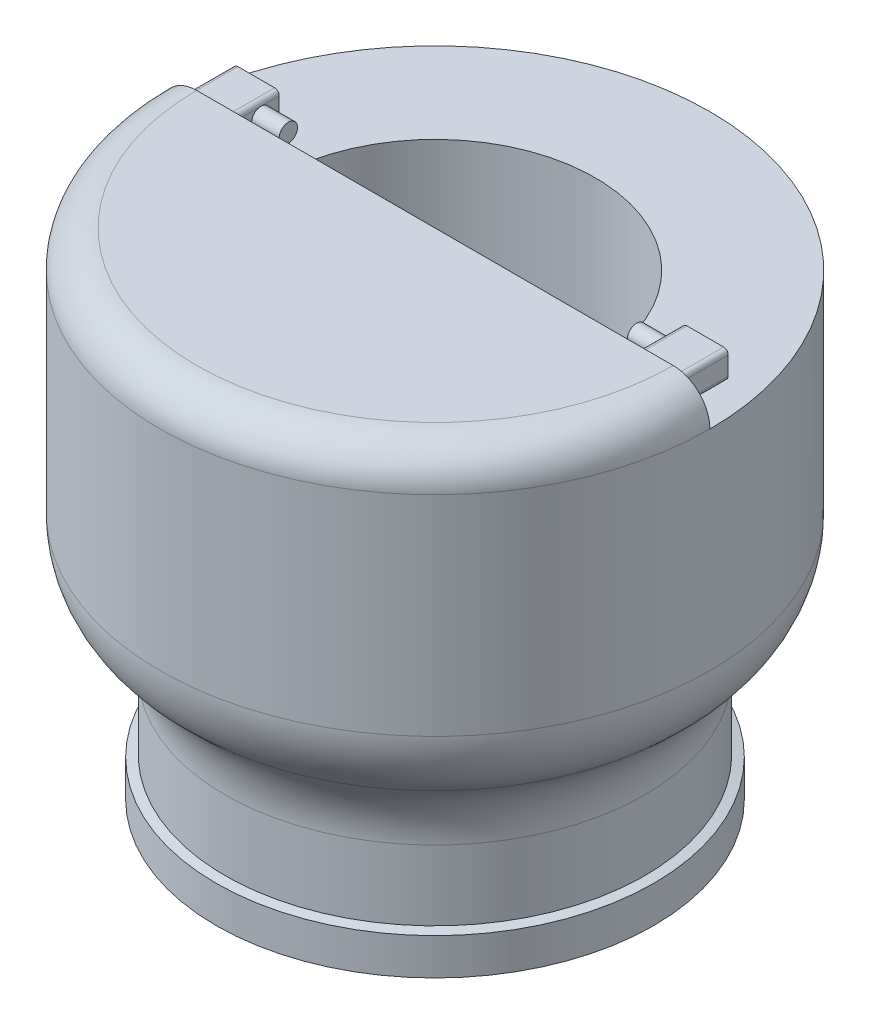
SolidWorks part; units mm, degrees
ref_plane "Front Plane" through (0, 0, 0) normal (0, 0, 1) x (1, 0, 0)
ref_plane "Top Plane" through (0, 0, 0) normal (0, 1, 0) x (1, 0, 0)
ref_plane "Right Plane" through (0, 0, 0) normal (1, 0, 0) x (0, 0, -1)
sketch "Sketch1" plane through (0, 0, 0) normal (0, 0, 1) x (1, 0, 0)
  line L0 (0, 0) -> (0, 57.8936) construction
  line L1 (20.9, 0) -> (23.8716, 0)
  line L2 (23.8716, 0) -> (23.8716, 4)
  line L3 (23.8716, 4) -> (22.9, 4.2367)
  line L4 (22.9, 4.2367) -> (22.9, 11.8746)
  line L6 (20.9, 0) -> (20.9, 14)
  line L12 (19.9, 15) -> (0, 15)
  line L17 (26.4721, 19.535) -> (26.4279, 19.4979)
  line L18 (30, 27.1583) -> (30, 50)
  line L20 (26, 54) -> (0, 54)
  line L22 (0, 15) -> (0, 54)
  arc A1 (30, 50) -> (26, 54) centre (26, 50) ccw
  arc A2 (26.4721, 19.535) -> (22.9, 11.8746) centre (32.9, 11.8746) ccw
  arc A3 (26.4279, 19.4979) -> (30, 27.1583) centre (20, 27.1583) ccw
  arc A6 (20.9, 14) -> (19.9, 15) centre (19.9, 14) ccw
  point P11 (22.9, 54)
  point P28 (28.5604, 23.4279)
  point P31 (20.9, 17)
  dimension "D9" = 4
  dimension "D4" = 30
  dimension "D16" = 10
  dimension "D19" = 1
  dimension "D2" = 4
  dimension "D3" = 1
  dimension "D6" = 2
  dimension "D7" = 2.9716
  dimension "D11" = 15
  dimension "D15" = 10
revolve "Revolve1" add sketch "Sketch1" angle 360 about L0
ref_plane "Plane1" through (0, 4, 0) normal (0, 1, 0) x (1, 0, 0)
sketch "Sketch3" plane through (0, 0, 0) normal (0, 0, 1) x (1, 0, 0)
  point P0 (1.2404, 19.1989)
ref_point "Point1"
ref_plane "Plane2" through (0, 0, 22.9) normal (0, 0, 1) x (1, 0, 0)
ref_plane "Plane3" through (0, 0, 30) normal (0, 0, 1) x (1, 0, 0)
ref_plane "Plane4" through (0, 50, 0) normal (0, -1, 0) x (-1, 0, 0)
sketch "Sketch9" plane through (0, 50, 0) normal (0, -1, 0) x (-1, 0, 0)
  line L0 (-30, 0) -> (30, 0)
  arc A0 (30, 0) -> (-30, 0) centre (0, 0) ccw
  circle A3 centre (0, 0) radius 26 construction
  dimension "D1" = 60
  dimension "D3" = 30
  dimension "D4" = 0
ref_plane "Plane5" through (0, 17, 0) normal (0, 1, 0) x (1, 0, 0)
sketch "Sketch11" plane through (0, 17, 0) normal (0, 1, 0) x (1, 0, 0)
  line L0 (-17.5, 0) -> (17.5, 0)
  arc A1 (-17.5, 0) -> (17.5, 0) centre (0, 0) cw
  dimension "D1" = 35
extrude "Cut-Extrude3" cut sketch "Sketch11" against normal blind 20 and the other way blind 45
ref_plane "Plane6" through (0, 0, -30) normal (0, 0, -1) x (-1, 0, 0)
extrude "Cut-Extrude5" cut sketch "Sketch9" against normal blind 5
sketch "Sketch13" plane through (0, 0, 0) normal (0, 0, -1) x (-1, 0, 0)
  line L0 (30, 49) -> (17.5, 49) construction
  line L1 (22.5, 53.5) -> (26.5, 53.5)
  line L2 (22, 53) -> (22, 51)
  line L3 (22.5, 50.5) -> (26.5, 50.5)
  line L4 (27, 53) -> (27, 51)
  line L5 (22, 53.5) -> (27, 50.5) construction
  line L6 (22, 50.5) -> (27, 53.5) construction
  line L7 (30, 49) -> (30, 50) construction
  line L8 (-30, 50) -> (-30, 49) construction
  line L9 (-26.5, 53.5) -> (-22.5, 53.5)
  line L10 (-27, 53) -> (-27, 51)
  line L11 (-26.5, 50.5) -> (-22.5, 50.5)
  line L12 (-22, 53) -> (-22, 51)
  line L13 (-27, 53.5) -> (-22, 50.5) construction
  line L14 (-27, 50.5) -> (-22, 53.5) construction
  line L15 (-17.5, 49) -> (-30, 49) construction
  arc A0 (26.5, 50.5) -> (27, 51) centre (26.5, 51) ccw
  arc A1 (27, 53) -> (26.5, 53.5) centre (26.5, 53) ccw
  arc A2 (22.5, 53.5) -> (22, 53) centre (22.5, 53) ccw
  arc A3 (22, 51) -> (22.5, 50.5) centre (22.5, 51) ccw
  arc A4 (-26.5, 53.5) -> (-27, 53) centre (-26.5, 53) ccw
  arc A5 (-27, 51) -> (-26.5, 50.5) centre (-26.5, 51) ccw
  arc A6 (-22.5, 50.5) -> (-22, 51) centre (-22.5, 51) ccw
  arc A7 (-22.5, 53.5) -> (-22, 53) centre (-22.5, 53) cw
  point P0 (24.5, 52)
  point P7 (-24.5, 52)
  dimension "D9" = 0.5
  dimension "D1" = 3
  dimension "D2" = 3
  dimension "D3" = 3
  dimension "D4" = 5
  dimension "D5" = 5
  dimension "D6" = 3
  dimension "D7" = 3
  dimension "D8" = 3
extrude "Boss-Extrude2" add sketch "Sketch13" along normal blind 5
sketch "Sketch14" plane through (22, 0, 0) normal (-1, 0, 0) x (0, 0, 1)
  line L0 (-5, 51) -> (0, 51) construction
  line L1 (-5, 51) -> (-5, 53) construction
  circle A0 centre (-3, 52) radius 1
  dimension "D1" = 2
  dimension "D2" = 1
  dimension "D3" = 2
extrude "Boss-Extrude3" add sketch "Sketch14" along normal blind 3
sketch "Sketch15" plane through (-22, 0, 0) normal (1, 0, 0) x (0, 0, -1)
  line L0 (5, 53) -> (0, 53) construction
  line L1 (5, 53) -> (5, 51) construction
  circle A0 centre (3, 52) radius 1
  dimension "D1" = 2
  dimension "D2" = 1
  dimension "D3" = 2
extrude "Boss-Extrude4" add sketch "Sketch15" along normal blind 3
sketch "Sketch16" plane through (0, 50, 0) normal (0, -1, 0) x (-1, 0, 0)
  line L0 (28.4704, -4) -> (-28.4704, -4)
  arc A0 (-28.4704, -4) -> (28.4704, -4) centre (0, 0) ccw
  arc A1 (-30, 0) -> (30, 0) centre (0, 0) ccw construction
  dimension "D1" = 1.25
  dimension "D2" = 4
  dimension "D3" = 4
extrude "Cut-Extrude6" cut sketch "Sketch16" along normal blind 22
sketch "Sketch18" plane through (0, 0, 0) normal (1, 0, 0) x (0, 0, -1)
  line L0 (-30, 28.173) -> (-28.5, 28.173)
  line L1 (-30, 12.5629) -> (-30, -12.5629) construction
  line L2 (-28.5, 28.173) -> (-28.5, 50)
  line L3 (-16.5, 50) -> (16.5, 50) construction
  line L4 (-28.5, 50) -> (-30, 50)
  line L5 (-30, 50) -> (-30, 28.173)
  line L7 (-28.5, 28.173) -> (1.0524, 28.173) construction
  dimension "D1" = 1.5
sketch "Sketch19" plane through (0, 50, 0) normal (0, -1, 0) x (-1, 0, 0)
  circle A0 centre (0, 0) radius 27.714 construction
